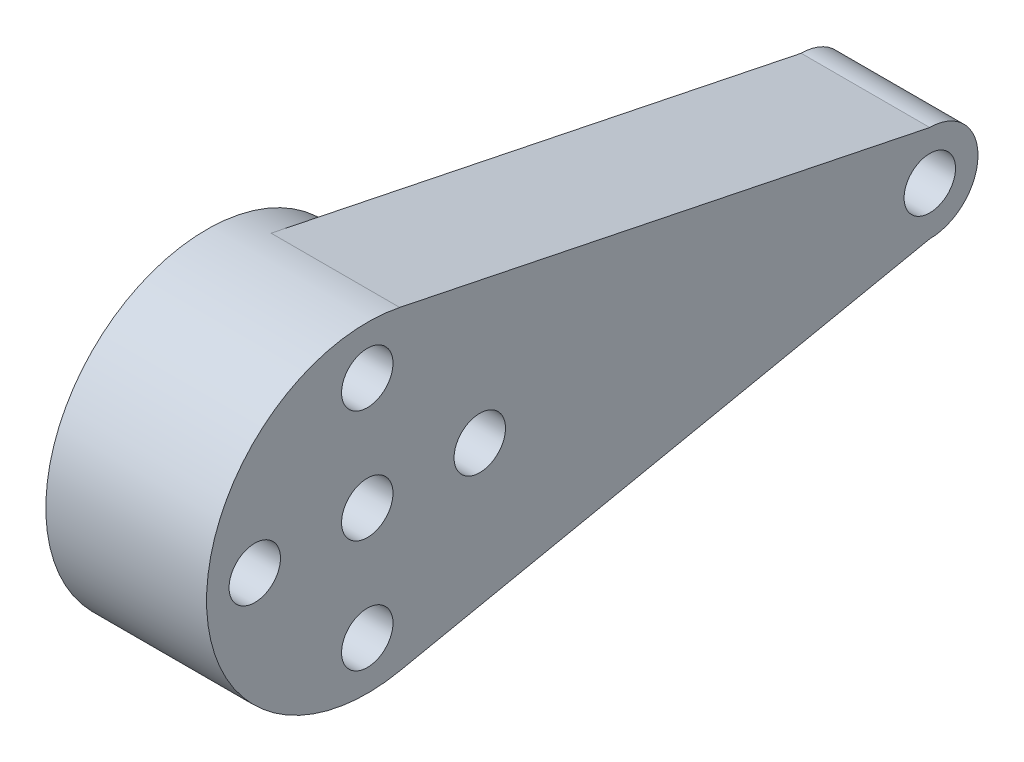
SolidWorks part; units mm, degrees
ref_plane "Plan de face" through (0, 0, 0) normal (0, 0, 1) x (1, 0, 0)
ref_plane "Plan de dessus" through (0, 0, 0) normal (0, 1, 0) x (1, 0, 0)
ref_plane "Plan de droite" through (0, 0, 0) normal (1, 0, 0) x (0, 0, -1)
sketch "Esquisse1" plane through (0, 0, 0) normal (1, 0, 0) x (0, 0, -1)
  circle A0 centre (0, 0) radius 10
  circle A1 centre (0, 0) radius 7 construction
  circle A2 centre (0, 7) radius 1.6
  circle A3 centre (7, 0) radius 1.6
  circle A4 centre (0, -7) radius 1.6
  circle A5 centre (-7, 0) radius 1.6
  circle A6 centre (0, 0) radius 1.6
  dimension "D1" = 14
  dimension "D2" = 20
  dimension "D3" = 3.2
  dimension "D4" = 4
extrude "Boss.-Extru.1" add sketch "Esquisse1" along normal blind 2
sketch "Esquisse2" plane through (2, 0, 0) normal (1, 0, 0) x (0, 0, -1)
  line L0 (2.0176, 9.7943) -> (35, 3)
  line L1 (35, -3) -> (2.0176, -9.7943)
  line L2 (2.0176, -9.7943) -> (-2.097, -10.642) construction
  line L3 (0, 10.21) -> (2.0176, 9.7943) construction
  circle A0 centre (35, 0) radius 3
  circle A1 centre (0, 7) radius 1.6 construction
  circle A2 centre (0, 0) radius 10
  circle A3 centre (0, 0) radius 10
  circle A4 centre (7, 0) radius 1.6 construction
  circle A5 centre (0, -7) radius 1.6 construction
  circle A6 centre (0, 0) radius 1.6 construction
  circle A7 centre (-7, 0) radius 1.6 construction
  circle A8 centre (0, 7) radius 1.6
  circle A9 centre (7, 0) radius 1.6
  circle A10 centre (0, -7) radius 1.6
  circle A11 centre (0, 0) radius 1.6
  circle A12 centre (-7, 0) radius 1.6
  circle A13 centre (35, 0) radius 1.6
  circle M8 centre (0, -7) radius 1.6
  circle M9 centre (0, 0) radius 1.6
  circle M10 centre (0, 0) radius 10
  circle M11 centre (0, 7) radius 1.6
  circle M12 centre (7, 0) radius 1.6
  circle M13 centre (-7, 0) radius 1.6
  dimension "D1" = 6
  dimension "D2" = 35
  dimension "D3" = 0
extrude "Boss.-Extru.2" add sketch "Esquisse2" along normal blind 8 and the other way blind 0.0001 contours M10 M9 M11 M13 M12 M8 | A0 L0 L1 M10 | A0 A13
